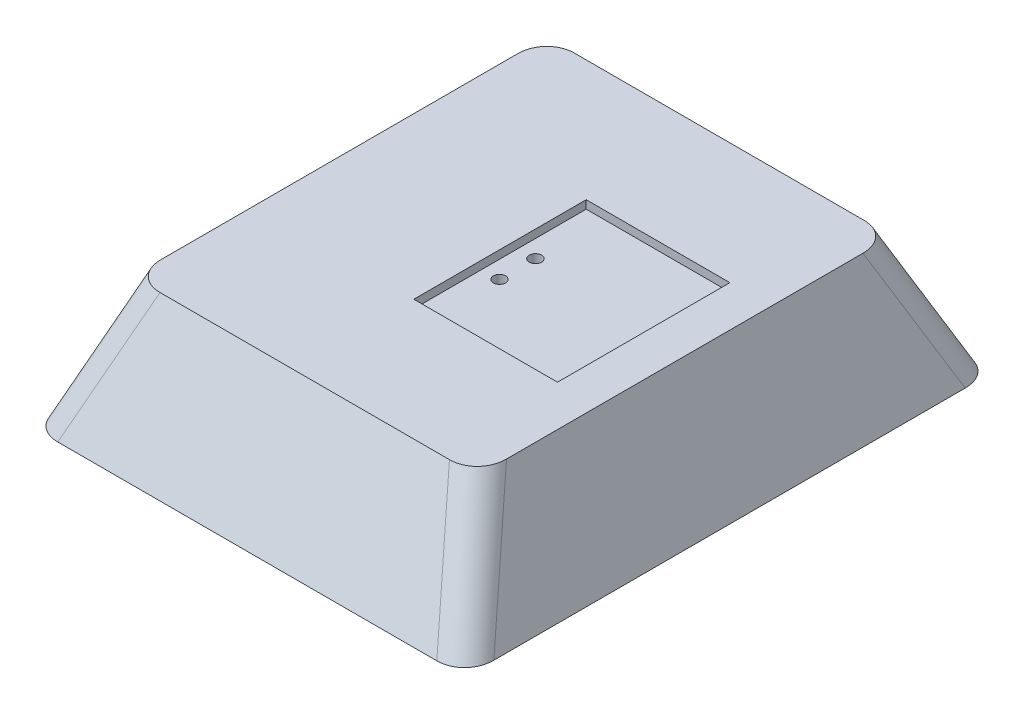
SolidWorks part; units mm, degrees
ref_plane "Front Plane" through (0, 0, 0) normal (0, 0, 1) x (1, 0, 0)
ref_plane "Top Plane" through (0, 0, 0) normal (0, 1, 0) x (1, 0, 0)
ref_plane "Right Plane" through (0, 0, 0) normal (1, 0, 0) x (0, 0, -1)
sketch "Master_Geometry" plane through (0, 0, 0) normal (0, 0, 1) x (1, 0, 0)
  line L0 (-48, -3.5) -> (-53, -3.5)
  line L1 (-47.5, -3.5) -> (47.5, -3.5) construction
  line L2 (-47.5, -3.5) -> (-47.5, 3.5) construction
  line L3 (-47.5, 3.5) -> (47.5, 3.5) construction
  line L4 (47.5, -3.5) -> (47.5, 3.5) construction
  line L5 (-47.5, -3.5) -> (47.5, 3.5) construction
  line L6 (-47.5, 3.5) -> (47.5, -3.5) construction
  line L7 (-53, -3.5) -> (-42.0809, 26.5)
  line L8 (-42.0809, 26.5) -> (42.0809, 26.5)
  line L13 (42.0809, 26.5) -> (53, -3.5)
  line L14 (53, -3.5) -> (48, -3.5)
  line L15 (48, -3.5) -> (48, 4)
  line L16 (48, 4) -> (38, 4)
  line L17 (38, 4) -> (38, 21.5)
  line L18 (38, 21.5) -> (-38, 21.5)
  line L19 (-38, 21.5) -> (-38, 4)
  line L20 (-38, 4) -> (-48, 4)
  line L21 (-48, 4) -> (-48, -3.5)
  point P0 (0, 0)
  dimension "D1" = 95
  dimension "D2" = 7
  dimension "D3" = 18
  dimension "D4" = 0.5
  dimension "D5" = 0.5
  dimension "D6" = 10
  dimension "D7" = 0.5
  dimension "D8" = 0.5
  dimension "D9" = 10
  dimension "D11" = 70
  dimension "D12" = 70
  dimension "D19" = 5
  dimension "D20" = 5
  dimension "D10" = 5
extrude "Top_Enclosure" add sketch "Master_Geometry" along normal blind 77
sketch "Sketch2" plane through (0, 0, 77) normal (0, 0, 1) x (1, 0, 0)
  line L0 (-42.0809, 26.5) -> (42.0809, 26.5)
  line L1 (42.0809, 26.5) -> (53, -3.5)
  line L2 (53, -3.5) -> (-53, -3.5)
  line L3 (-53, -3.5) -> (-42.0809, 26.5)
extrude "Top_Extra" add sketch "Sketch2" along normal blind 12
ref_plane "Plane_Symm" through (0, 0, 38.5) normal (0, 0, -1) x (-1, 0, 0)
mirror "Mirror1" about plane through (0, 0, 38.5) normal (0, 0, -1) of "Top_Extra"
sketch "Sketch3" plane through (0, 26.5, 0) normal (0, 1, 0) x (1, 0, 0)
  line L0 (13.75, -38.5) -> (-13.75, -38.5) construction
  line L1 (-2.9191, -59.5) -> (32.0809, -59.5)
  line L2 (-2.9191, -59.5) -> (-2.9191, -17.5)
  line L3 (-2.9191, -17.5) -> (32.0809, -17.5)
  line L4 (32.0809, -59.5) -> (32.0809, -17.5)
  line L5 (-2.9191, -59.5) -> (32.0809, -17.5) construction
  line L6 (-2.9191, -17.5) -> (32.0809, -59.5) construction
  line L7 (42.0809, -89) -> (42.0809, 12) construction
  point P0 (14.5809, -38.5)
  dimension "D1" = 35
  dimension "D2" = 42
  dimension "D3" = 10
extrude "Solar_Cell_Slot" cut sketch "Sketch3" against normal blind 2
sketch "Sketch4" plane through (0, 24.5, 0) normal (0, 1, 0) x (1, 0, 0)
  line L1 (-2.9191, -38.5) -> (32.0809, -38.5) construction
  line L2 (13.75, -38.5) -> (-13.75, -38.5) construction
  line L3 (-2.9191, -17.5) -> (-2.9191, -59.5) construction
  line L4 (32.0809, -59.5) -> (32.0809, -17.5) construction
  circle A0 centre (1.3309, -34.125) radius 1.5
  circle A1 centre (1.3309, -42.875) radius 1.5
  point P6 (33.1191, -38.5)
  point P7 (-1.9191, -38.5)
  point P12 (0, 0)
  point P13 (-1.9191, -38.5)
  point P14 (0, 0)
  dimension "D2" = 3
  dimension "D3" = 3
  dimension "D1" = 8.75
  dimension "D4" = 4.25
extrude "Solar_Cell_Holes" cut sketch "Sketch4" against normal through all
sketch "Sketch5" plane through (0, 0, 0) normal (1, 0, 0) x (0, 0, -1)
  line L0 (-89, 26.5) -> (-89, -3.5)
  line L1 (-89, -3.5) -> (-102.9892, -3.5)
  line L2 (-102.9892, -3.5) -> (-89, 26.5)
  dimension "D1" = 65
extrude "Boss-Extrude1" add sketch "Sketch5" along normal up to surface (53 mm away)
sketch "Sketch6" plane through (0, 0, 0) normal (-1, 0, 0) x (0, 0, 1)
  line L0 (89, 26.5) -> (102.9892, -3.5)
  line L1 (102.9892, -3.5) -> (89, -3.5)
  line L2 (89, -3.5) -> (89, 26.5)
extrude "Boss-Extrude2" add sketch "Sketch6" along normal up to surface (42.0809 mm away) contours L2 L0 L1
mirror "Mirror3" about plane through (0, 0, 38.5) normal (0, 0, -1) of "Boss-Extrude2", "Boss-Extrude1"
fillet "Fillet1" radius 7.5 4 edges at (-47.5404, 11.5, 95.9946) (47.5404, 11.5, -18.9946) (-47.5404, 11.5, -18.9946) (47.5404, 11.5, 95.9946)
equation "\"rel_tol\"= 0.5mm"
equation "\"dist_pcb_top\"= 18mm"
equation "\"enclosure_angle\"= 70deg"
equation "\"solar_cell_x\"= 42mm"
equation "\"solar_cell_y\"= 35mm"
equation "\"solar_cell_z\"= 2mm"
equation "\"top_extra\"= 10mm"
equation "\"top_thickness\"= 5mm"
equation "\"top_extra_bottom\"= 5mm"
equation "\"solar_cell_pos\"= 35mm"
equation "\"bottom_overall_x\"= 95mm"
equation "\"bottom_overall_y\"= 7mm"
equation "\"D1@Master_Geometry\" = \"bottom_overall_x\""
equation "\"D3@Master_Geometry\" = \"dist_pcb_top\""
equation "\"D4@Master_Geometry\" = \"rel_tol\""
equation "\"D5@Master_Geometry\" = \"rel_tol\""
equation "\"D6@Master_Geometry\" = \"top_extra\""
equation "\"D7@Master_Geometry\" = \"rel_tol\""
equation "\"D8@Master_Geometry\" = \"rel_tol\""
equation "\"D9@Master_Geometry\" = \"top_extra\""
equation "\"D11@Master_Geometry\" = \"enclosure_angle\""
equation "\"D12@Master_Geometry\" = \"enclosure_angle\""
equation "\"D19@Master_Geometry\" = \"top_extra_bottom\""
equation "\"D20@Master_Geometry\" = \"top_extra_bottom\""
equation "\"pcb_length\"= 90mm"
equation "\"pcb_width\"= 65mm"
equation "\"D1@Top_Enclosure\"=\"pcb_width\" +  ( 4 * \"rel_tol\" ) + (2 * 5)"
equation "\"D10@Master_Geometry\" = \"top_thickness\""
equation "\"top_extra_outside\"= 12mm"
equation "\"D1@Top_Extra\" = \"top_extra_outside\""
equation "\"D1@Sketch3\"=\"solar_cell_y\""
equation "\"D2@Sketch3\"=\"solar_cell_x\""
equation "\"D1@Solar_Cell_Slot\" = \"solar_cell_z\""
equation "\"flatter_region\"= 65deg"
equation "\"D1@Sketch5\"=\"flatter_region\""
